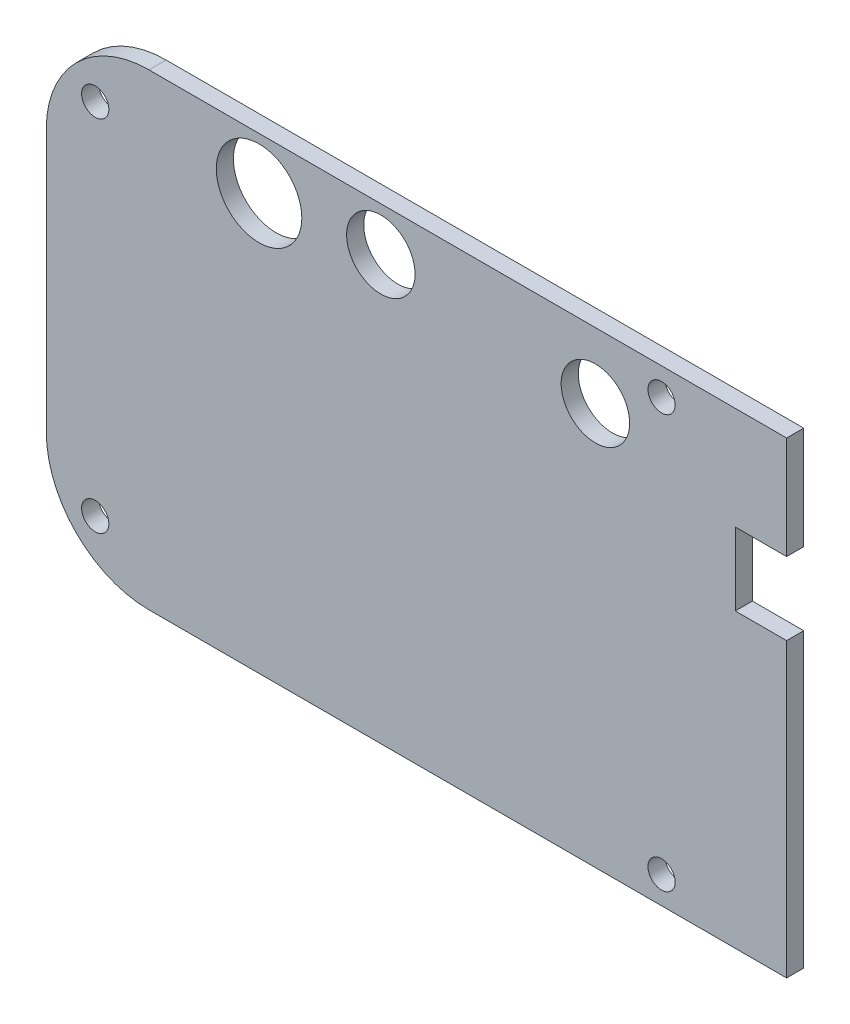
SolidWorks part; units mm, degrees
ref_plane "Plano frontal" through (0, 0, 0) normal (0, 0, 1) x (1, 0, 0)
ref_plane "Plano superior" through (0, 0, 0) normal (0, 1, 0) x (1, 0, 0)
ref_plane "Plano direito" through (0, 0, 0) normal (1, 0, 0) x (0, 0, -1)
sketch "Esboço1" plane through (0, 0, 0) normal (0, 0, 1) x (1, 0, 0)
  line L0 (0, 0) -> (86.5, 0)
  line L1 (86.5, 0) -> (86.5, 54.64)
  line L2 (86.5, 54.64) -> (0, 54.64)
  line L3 (0, 54.64) -> (0, 0)
  dimension "D1" = 86.5
  dimension "D2" = 54.64
extrude "Ressalto-extrusão2" add sketch "Esboço1" along normal blind 2 contours L2 L3 L0 L1
sketch "Esboço3" plane through (0, 0, 0) normal (0, 0, -1) x (-1, 0, 0)
  line L0 (-86.5, 0) -> (-86.5, 54.64) construction
  line L1 (-86.5, 54.64) -> (0, 54.64) construction
  line L2 (0, 0) -> (-86.5, 0) construction
  line L3 (0, 54.64) -> (0, 0) construction
  circle A0 centre (-71.89, 51.46) radius 1.59
  circle A1 centre (-71.89, 3.18) radius 1.59
  circle A2 centre (-5.72, 6.35) radius 1.59
  circle A3 centre (-5.72, 48.29) radius 1.59
  dimension "D3" = 3.18
  dimension "D4" = 3.18
  dimension "D10" = 3.18
  dimension "D11" = 3.18
  dimension "D1" = 14.61
  dimension "D2" = 3.18
  dimension "D5" = 14.61
  dimension "D6" = 3.18
  dimension "D7" = 5.72
  dimension "D8" = 5.72
  dimension "D9" = 6.35
  dimension "D12" = 6.35
extrude "Corte-extrusão1" cut sketch "Esboço3" against normal blind 2
fillet "Filete1" radius 12 1 edges at (0, 54.64, 1)
fillet "Filete2" radius 12 1 edges at (0, 0, 1)
sketch "Esboço4" plane through (0, 0, 2) normal (0, 0, 1) x (1, 0, 0)
  line L0 (86.5, 54.64) -> (12, 54.64) construction
  line L1 (0, 42.64) -> (0, 12) construction
  line L2 (86.5, 0) -> (86.5, 54.64) construction
  line L3 (86.5, 42.64) -> (80.5, 42.64)
  line L4 (80.5, 42.64) -> (80.5, 34.14)
  line L5 (80.5, 34.14) -> (86.5, 34.14)
  line L6 (86.5, 34.14) -> (86.5, 42.64)
  circle A0 centre (24.86, 48.58) radius 5
  circle A1 centre (39.09, 49.5) radius 4
  circle A2 centre (64.16, 46.97) radius 4
  dimension "D1" = 6.06
  dimension "D3" = 10
  dimension "D4" = 8
  dimension "D5" = 5.14
  dimension "D9" = 8
  dimension "D2" = 24.86
  dimension "D6" = 47.41
  dimension "D7" = 7.67
  dimension "D8" = 22.34
  dimension "D10" = 12
  dimension "D11" = 8.5
  dimension "D12" = 6
extrude "Corte-extrusão2" cut sketch "Esboço4" against normal blind 10
